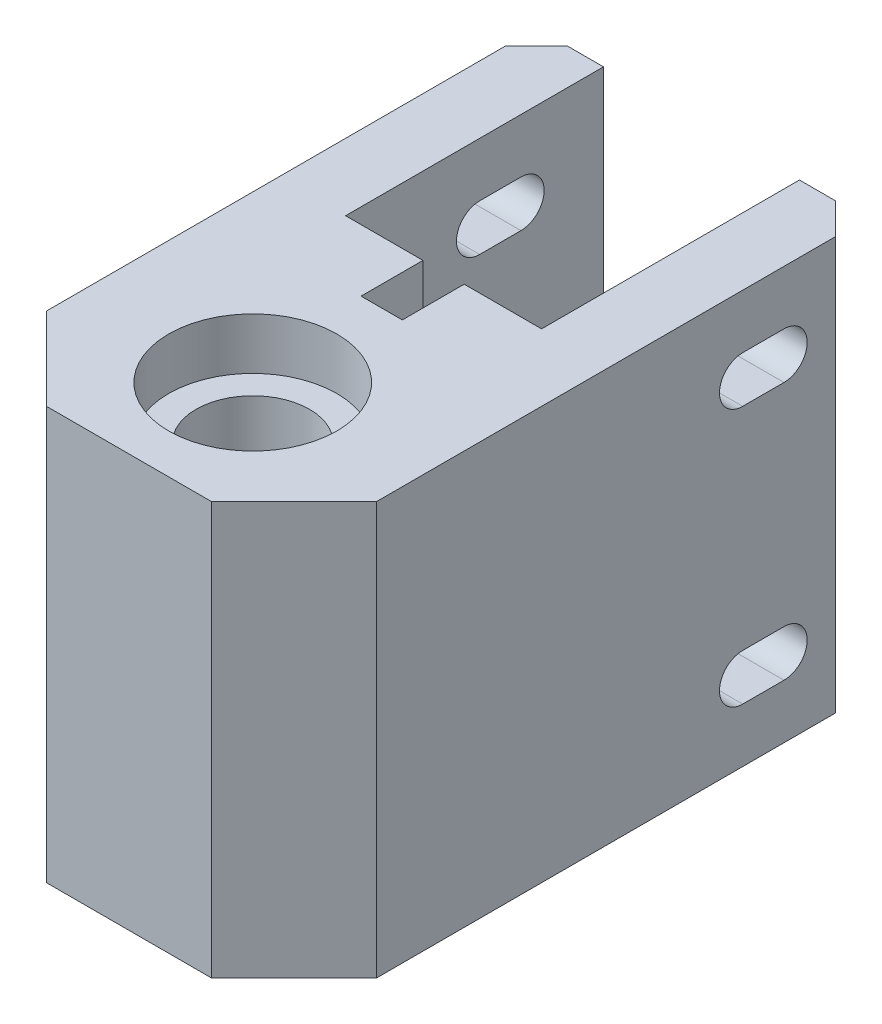
SolidWorks part; units mm, degrees
material "3D printed plastic"
ref_plane "Front Plane" through (0, 0, 0) normal (0, 0, 1) x (1, 0, 0)
ref_plane "Top Plane" through (0, 0, 0) normal (0, 1, 0) x (1, 0, 0)
ref_plane "Right Plane" through (0, 0, 0) normal (1, 0, 0) x (0, 0, -1)
sketch "Sketch1" plane through (0, 0, 0) normal (0, 1, 0) x (1, 0, 0)
  line L0 (0, 0) -> (0, 18.5) construction
  line L1 (-9.5, 43.5) -> (9.5, 43.5) construction
  line L2 (-9.5, 43.5) -> (-9.5, 18.5)
  line L3 (-9.5, 18.5) -> (-2, 18.5)
  line L4 (9.5, 43.5) -> (9.5, 18.5)
  line L5 (-9.5, 43.5) -> (-13, 43.5)
  line L6 (-13, 43.5) -> (-16, 40.5)
  line L7 (-16, 40.5) -> (-16, -4)
  line L8 (-16, -4) -> (-8, -12)
  line L9 (-8, -12) -> (8, -12)
  line L10 (8, -12) -> (16, -4)
  line L11 (16, -4) -> (16, 40.5)
  line L12 (16, 40.5) -> (13, 43.5)
  line L13 (13, 43.5) -> (9.5, 43.5)
  line L14 (2, 18.5) -> (9.5, 18.5)
  line L15 (-2, 18.5) -> (2, 18.5) construction
  line L16 (-2, 18.5) -> (-2, 12.5)
  line L17 (-2, 12.5) -> (2, 12.5)
  line L18 (2, 18.5) -> (2, 12.5)
  circle A0 centre (0, 0) radius 5.5
  dimension "D1" = 11
  dimension "D2" = 19
  dimension "D3" = 18.5
  dimension "D4" = 25
  dimension "D5" = 3
  dimension "D6" = 45
  dimension "D7" = 32
  dimension "D8" = 12
  dimension "D9" = 8
  dimension "D10" = 4
  dimension "D11" = 6
extrude "Boss-Extrude1" add sketch "Sketch1" along normal mid plane 40
sketch "Sketch2" plane through (0, 20, 0) normal (0, 1, 0) x (1, 0, 0)
  circle A0 centre (0, 0) radius 8.15
  dimension "D1" = 16.3
extrude "Cut-Extrude1" cut sketch "Sketch2" against normal blind 5
mirror "Mirror1" about plane through (0, 0, 0) normal (0, 1, 0) of "Cut-Extrude1"
sketch "Sketch3" plane through (16, 0, 0) normal (1, 0, 0) x (0, 0, -1)
  line L0 (33.5, -12.5) -> (33.5, 12.5) construction
  line L1 (35.5, 12.5) -> (31.5, 12.5) construction
  line L2 (35.5, 10.25) -> (31.5, 10.25)
  line L3 (35.5, 14.75) -> (31.5, 14.75)
  line L4 (35.5, -12.5) -> (31.5, -12.5) construction
  line L5 (35.5, -14.75) -> (31.5, -14.75)
  line L6 (35.5, -10.25) -> (31.5, -10.25)
  line L7 (33.5, 0) -> (0, 0) construction
  line L8 (18.5, 20) -> (18.5, -20) construction
  arc A0 (35.5, 10.25) -> (35.5, 14.75) centre (35.5, 12.5) ccw
  arc A1 (31.5, 14.75) -> (31.5, 10.25) centre (31.5, 12.5) ccw
  arc A2 (35.5, -14.75) -> (35.5, -10.25) centre (35.5, -12.5) ccw
  arc A3 (31.5, -10.25) -> (31.5, -14.75) centre (31.5, -12.5) ccw
  point P4 (33.5, 12.5)
  point P10 (33.5, -12.5)
  dimension "D1" = 4
  dimension "D2" = 4.5
  dimension "D3" = 25
  dimension "D4" = 15
extrude "Cut-Extrude2" cut sketch "Sketch3" against normal through all
